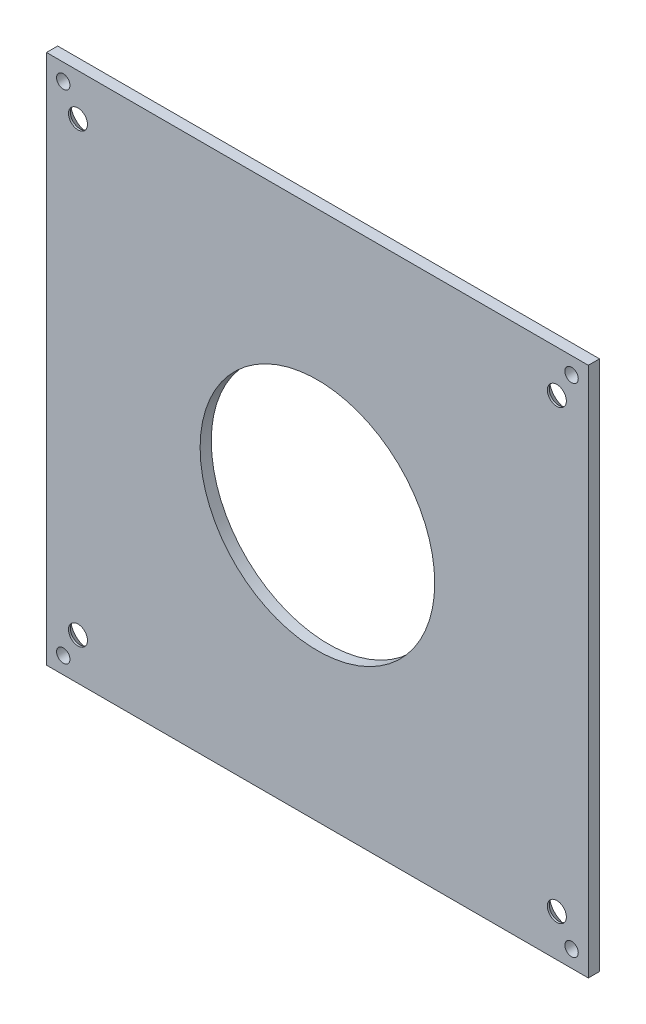
SolidWorks part; units mm, degrees
material "6061-T6 (SS)"
ref_plane "Front Plane" through (0, 0, 0) normal (0, 0, 1) x (1, 0, 0)
ref_plane "Top Plane" through (0, 0, 0) normal (0, 1, 0) x (1, 0, 0)
ref_plane "Right Plane" through (0, 0, 0) normal (1, 0, 0) x (0, 0, -1)
sketch "Plate sketch" plane through (0, 0, 0) normal (0, 0, 1) x (1, 0, 0)
  line L1 (0, 0) -> (97, 0)
  line L2 (0, 0) -> (0, 95)
  line L3 (0, 95) -> (97, 95)
  line L4 (97, 0) -> (97, 95)
  dimension "D1" = 97
  dimension "D2" = 95
extrude "Plate" add sketch "Plate sketch" along normal blind 2
sketch "M2 foot screw holes sketch" plane through (0, 0, 0) normal (0, 0, 1) x (1, 0, 0)
  circle A0 centre (3, 3) radius 1.2
  circle A1 centre (94, 3) radius 1.2
  circle A2 centre (3, 92) radius 1.2
  circle A3 centre (94, 92) radius 1.2
extrude "M2 foot screw holes" cut sketch "M2 foot screw holes sketch" against normal through all and the other way through all
sketch "M3 stack rod holes sketch" plane through (0, 0, 0) normal (0, 0, 1) x (1, 0, 0)
  circle A0 centre (5.635, 7.495) radius 1.7
  circle A1 centre (91.365, 7.495) radius 1.7
  circle A2 centre (5.635, 87.505) radius 1.7
  circle A3 centre (91.365, 87.505) radius 1.7
extrude "M3 stack rod holes" cut sketch "M3 stack rod holes sketch" against normal through all and the other way through all
chamfer "M3 countersinks" distance 1.66 angle 45 4 edges at (3.935, 7.495, 0) (89.665, 87.505, 0) (3.935, 87.505, 0) (89.665, 7.495, 0)
sketch "Camera aperture sketch" plane through (0, 0, 0) normal (0, 0, 1) x (1, 0, 0)
  circle A0 centre (48.5, 47.5) radius 21
extrude "Camera aperture" cut sketch "Camera aperture sketch" against normal through all and the other way through all
